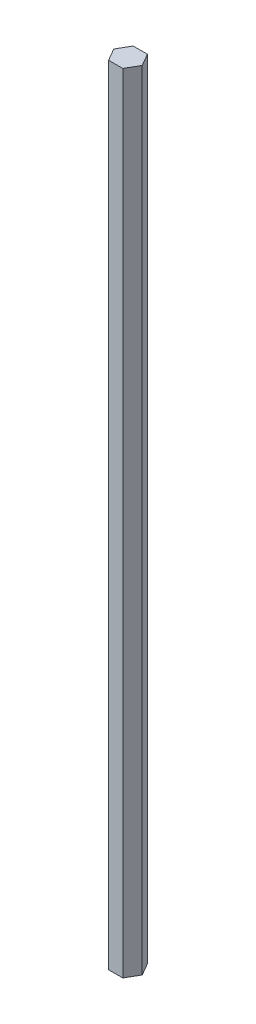
SolidWorks part; units mm, degrees
ref_plane "Front Plane" through (0, 0, 0) normal (0, 0, 1) x (1, 0, 0)
ref_plane "Top Plane" through (0, 0, 0) normal (0, 1, 0) x (1, 0, 0)
ref_plane "Right Plane" through (0, 0, 0) normal (1, 0, 0) x (0, 0, -1)
sketch "Sketch1" plane through (0, 0, 0) normal (0, 1, 0) x (1, 0, 0)
  line L1 (7.3323, 0) -> (3.6662, 6.35)
  line L2 (3.6662, 6.35) -> (-3.6662, 6.35)
  line L3 (-3.6662, 6.35) -> (-7.3323, 0)
  line L4 (-7.3323, 0) -> (-3.6662, -6.35)
  line L5 (-3.6662, -6.35) -> (3.6662, -6.35)
  line L6 (3.6662, -6.35) -> (7.3323, 0)
  circle A0 centre (0, 0) radius 6.35 construction
  point P1 (0, 0)
  dimension "D1" = 12.7
extrude "Boss-Extrude1" add sketch "Sketch1" along normal blind 406.4
